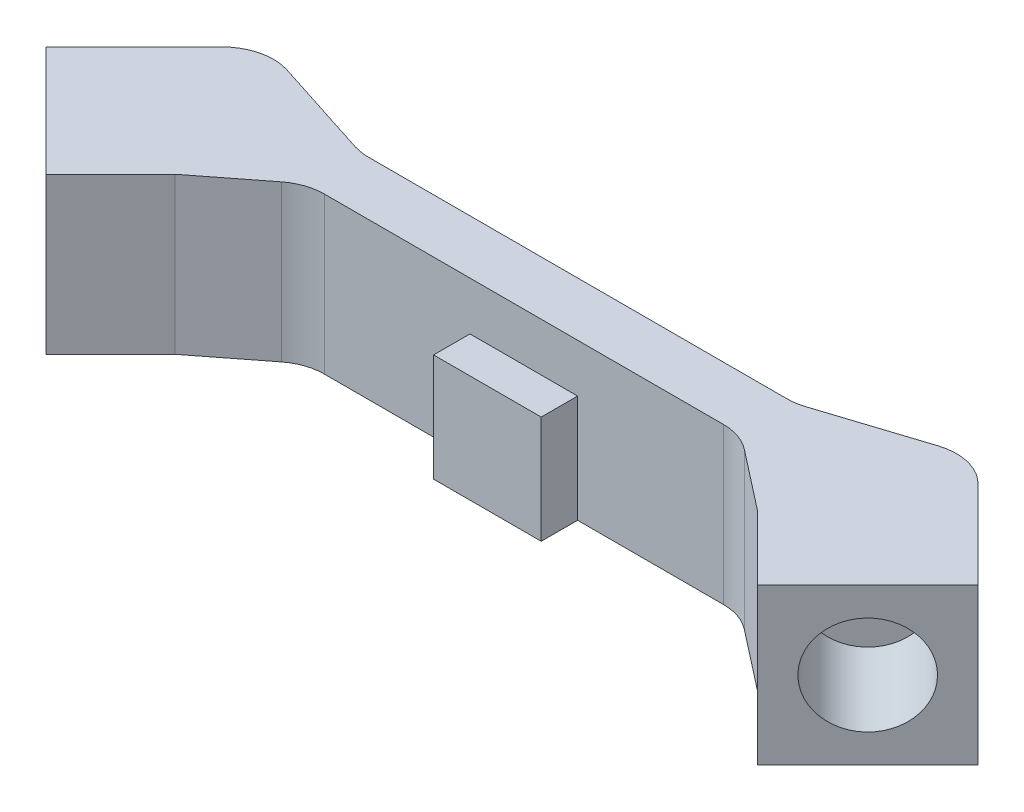
SolidWorks part; units mm, degrees
ref_plane "Front Plane" through (0, 0, 0) normal (0, 0, 1) x (1, 0, 0)
ref_plane "Top Plane" through (0, 0, 0) normal (0, 1, 0) x (1, 0, 0)
ref_plane "Right Plane" through (0, 0, 0) normal (1, 0, 0) x (0, 0, -1)
sketch "Sketch1" plane through (0, 0, 0) normal (0, 1, 0) x (1, 0, 0)
  line L0 (-8.395, 35.7208) -> (16.1076, 27.8284)
  line L5 (0, 0) -> (-15.7815, -15.7815)
  line L6 (-42.7223, 11.1592) -> (-15.7815, -15.7815)
  line L7 (71.12, 38.1) -> (71.12, 0) construction
  line L11 (-21.2689, 32.6126) -> (-42.7223, 11.1592)
  line L12 (20.0013, 27.2168) -> (122.2387, 27.2168)
  line L18 (14.5632, 11.3563) -> (0, 0)
  line L19 (22.3728, 14.0414) -> (119.8672, 14.0414)
  line L20 (142.24, 0) -> (158.0215, -15.7815)
  line L21 (127.6768, 11.3563) -> (142.24, 0)
  line L22 (150.635, 35.7208) -> (126.1324, 27.8284)
  line L23 (163.5089, 32.6126) -> (184.9623, 11.1592)
  line L24 (184.9623, 11.1592) -> (158.0215, -15.7815)
  arc A0 (22.3728, 14.0414) -> (14.5632, 11.3563) centre (22.3728, 1.3414) ccw
  arc A1 (16.1076, 27.8284) -> (20.0013, 27.2168) centre (20.0013, 39.9168) ccw
  arc A2 (-21.2689, 32.6126) -> (-8.395, 35.7208) centre (-12.2886, 23.6324) cw
  arc A3 (126.1324, 27.8284) -> (122.2387, 27.2168) centre (122.2387, 39.9168) cw
  arc A4 (119.8672, 14.0414) -> (127.6768, 11.3563) centre (119.8672, 1.3414) cw
  arc A5 (163.5089, 32.6126) -> (150.635, 35.7208) centre (154.5286, 23.6324) ccw
  point P14 (71.12, 27.2168)
  point P21 (-15.7815, 38.1)
  point P22 (71.12, 14.0414)
  dimension "D2" = 12.7
  dimension "D3" = 38.1
  dimension "D4" = 90
  dimension "D5" = 38.1
  dimension "D6" = 90
  dimension "D7" = 38.1
extrude "Boss-Extrude1" add sketch "Sketch1" along normal blind 38.1
sketch "Sketch2" plane through (-15.7815, 0, 15.7815) normal (-0.7071, 0, 0.7071) x (0.7071, 0, 0.7071)
  line L0 (-38.1, 38.1) -> (0, 0) construction
  line L1 (-38.1, 0) -> (0, 38.1) construction
  circle A0 centre (-19.05, 19.05) radius 12.065
  dimension "D1" = 24.13
extrude "Cut-Extrude1" cut sketch "Sketch2" against normal blind 25.4
sketch "Sketch7" plane through (86.9015, 0, 86.9015) normal (0.7071, 0, 0.7071) x (0.7071, 0, -0.7071)
  line L0 (119.6289, 38.1) -> (119.6289, 0) construction
  line L1 (100.5789, 38.1) -> (138.6789, 38.1) construction
  line L2 (100.5789, 0) -> (138.6789, 0) construction
  line L3 (119.6289, 0) -> (100.5789, 19.05) construction
  line L4 (100.5789, 38.1) -> (100.5789, 0) construction
  line L5 (100.5789, 19.05) -> (138.6789, 19.05) construction
  line L6 (138.6789, 38.1) -> (138.6789, 0) construction
  circle A0 centre (119.6289, 19.05) radius 12.065
  dimension "D1" = 24.13
extrude "Cut-Extrude2" cut sketch "Sketch7" against normal blind 25.4
sketch "Sketch8" plane through (0, 0, -14.0414) normal (0, 0, 1) x (1, 0, 0)
  line L0 (71.12, 38.1) -> (71.12, 0) construction
  line L1 (22.3728, 38.1) -> (119.8672, 38.1) construction
  line L2 (22.3728, 0) -> (119.8672, 0) construction
  line L3 (57.9755, 0) -> (57.9755, 26.289)
  line L4 (57.9755, 26.289) -> (84.2645, 26.289)
  line L5 (84.2645, 26.289) -> (84.2645, 0)
  line L10 (22.3728, 0) -> (119.8672, 0)
  line L11 (119.8672, 0) -> (119.8672, 38.1)
  line L12 (119.8672, 38.1) -> (22.3728, 38.1)
  line L13 (22.3728, 38.1) -> (22.3728, 0)
  line L14 (57.9755, 0) -> (84.2645, 0)
  dimension "D1" = 26.289
  dimension "D2" = 0
  dimension "D3" = 26.289
  dimension "D4" = 26.289
  dimension "D5" = 90
  dimension "D6" = 13.1445
extrude "Boss-Extrude2" add sketch "Sketch8" along normal blind 8.89
